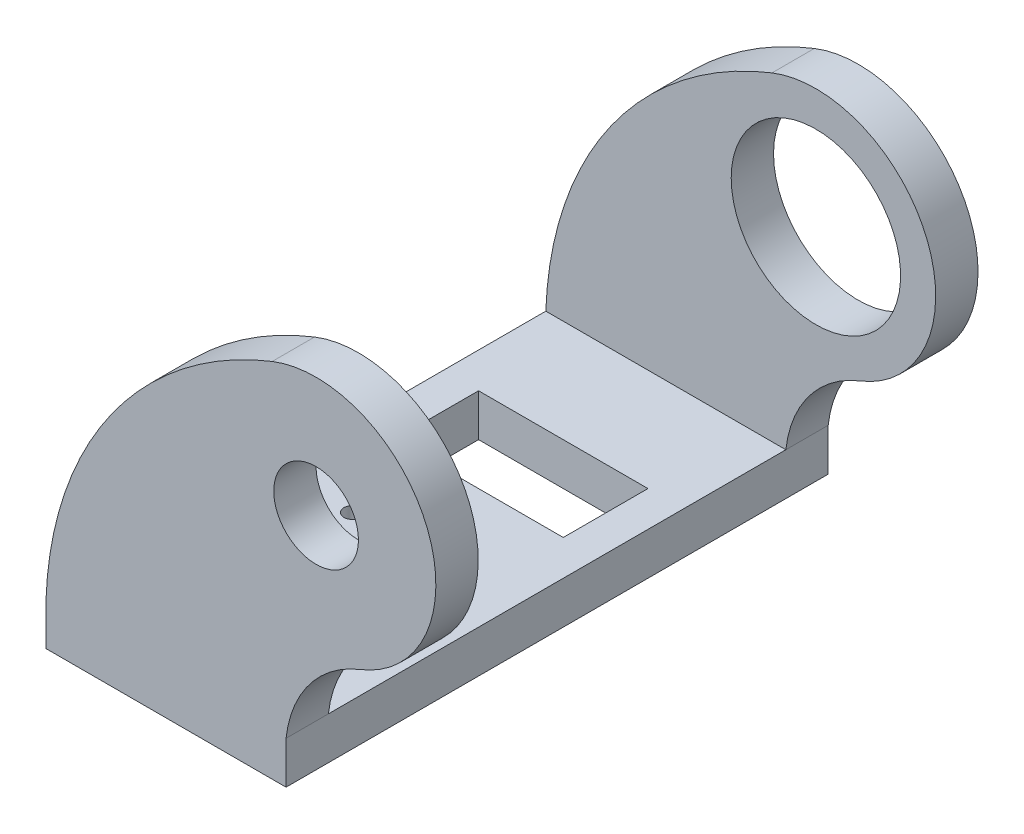
SolidWorks part; units mm, degrees
ref_plane "Front Plane" through (0, 0, 0) normal (0, 0, 1) x (1, 0, 0)
ref_plane "Top Plane" through (0, 0, 0) normal (0, 1, 0) x (1, 0, 0)
ref_plane "Right Plane" through (0, 0, 0) normal (1, 0, 0) x (0, 0, -1)
sketch "Model" plane through (0, 0, 0) normal (0, 0, 1) x (1, 0, 0)
  line L0 (25.204, 18.4188) -> (53.5459, 18.4188)
  arc A0 (51.9109, 56.1349) -> (25.204, 18.4188) centre (67.3687, 16.8755) ccw
  arc A1 (62.2731, 29.8172) -> (53.5459, 18.4188) centre (67.3687, 16.8755) ccw
  arc A2 (62.2731, 29.8172) -> (51.9109, 56.1349) centre (57.092, 42.9761) ccw
extrude "Boss-Extrude1" add sketch "Model" along normal blind 5
sketch "Sketch2" plane through (0, 0, 5) normal (0, 0, 1) x (1, 0, 0)
  circle A0 centre (57.092, 42.9761) radius 5
  dimension "D1" = 10
extrude "Cut-Extrude1" cut sketch "Sketch2" against normal blind 5
sketch "Sketch4" plane through (0, 18.4188, 0) normal (0, -1, 0) x (1, 0, 0)
  line L4 (25.204, 0) -> (53.5459, 0)
  line L5 (53.5459, 0) -> (53.5459, 5)
  line L6 (53.5459, 5) -> (25.204, 5)
  line L7 (25.204, 5) -> (25.204, 0)
  line L8 (25.204, 0) -> (53.5459, 0)
  line L9 (53.5459, 0) -> (53.5459, 5)
  line L10 (53.5459, 5) -> (25.204, 5)
  line L11 (25.204, 5) -> (25.204, 0)
  dimension "D1" = 0
extrude "Boss-Extrude2" add sketch "Sketch4" along normal blind 5
sketch "Sketch5" plane through (0, 0, 0) normal (0, 0, -1) x (-1, 0, 0)
  line L0 (-25.204, 13.4188) -> (-25.204, 18.4188) construction
  line L1 (-53.5459, 13.4188) -> (-25.204, 13.4188)
  line L2 (-53.5459, 13.4188) -> (-53.5459, 18.4188)
  line L3 (-53.5459, 18.4188) -> (-25.204, 18.4188)
  line L4 (-25.204, 13.4188) -> (-25.204, 18.4188)
extrude "Boss-Extrude3" add sketch "Sketch5" along normal blind 31.9
sketch "Sketch6" plane through (0, 18.4188, 0) normal (0, 1, 0) x (1, 0, 0)
  line L0 (39.3749, 31.9) -> (39.3749, 26.9) construction
  line L1 (25.204, 31.9) -> (53.5459, 31.9) construction
  line L3 (49.3749, 26.9) -> (29.3749, 26.9)
  line L4 (49.3749, 26.9) -> (49.3749, 31.9)
  line L5 (49.3749, 31.9) -> (29.3749, 31.9)
  line L6 (29.3749, 26.9) -> (29.3749, 31.9)
  line L7 (49.3749, 26.9) -> (29.3749, 31.9) construction
  line L8 (49.3749, 31.9) -> (29.3749, 26.9) construction
  point P4 (39.3749, 29.4)
extrude "Cut-Extrude3" cut sketch "Sketch6" against normal blind 5
sketch "Sketch8" plane through (0, 0, -31.9) normal (0, 0, -1) x (-1, 0, 0)
  line L1 (-53.5459, 18.4188) -> (-49.3749, 18.4188)
  line L2 (-53.5459, 18.4188) -> (-53.5459, 13.4188)
  line L3 (-53.5459, 13.4188) -> (-49.3749, 13.4188)
  line L4 (-25.204, 18.4188) -> (-29.3749, 18.4188)
  line L5 (-29.3749, 18.4188) -> (-29.3749, 13.4188)
  line L6 (-29.3749, 13.4188) -> (-25.204, 13.4188)
  line L7 (-25.204, 13.4188) -> (-25.204, 18.4188)
  line L8 (-25.204, 18.4188) -> (-29.3749, 18.4188)
  line L9 (-29.3749, 18.4188) -> (-29.3749, 13.4188)
  line L10 (-29.3749, 13.4188) -> (-25.204, 13.4188)
  line L11 (-25.204, 13.4188) -> (-25.204, 18.4188)
  line L12 (-49.3749, 18.4188) -> (-49.3749, 13.4188)
  dimension "D1" = 0
sketch "Sketch10" plane through (0, 18.4188, 0) normal (0, 1, 0) x (1, 0, 0)
  line L0 (39.3749, 26.9) -> (39.3749, 13.5) construction
  line L1 (29.3749, 26.9) -> (49.3749, 26.9) construction
  line L3 (44.3749, 10) -> (34.3749, 10) construction
  line L4 (44.3749, 10) -> (44.3749, 17) construction
  line L5 (44.3749, 17) -> (34.3749, 17) construction
  line L6 (34.3749, 10) -> (34.3749, 17) construction
  line L7 (44.3749, 10) -> (34.3749, 17) construction
  line L8 (44.3749, 17) -> (34.3749, 10) construction
  circle A0 centre (34.3749, 17) radius 1
  circle A1 centre (44.3749, 17) radius 1
  circle A2 centre (34.3749, 10) radius 1
  circle A3 centre (44.3749, 10) radius 1
extrude "Boss-Extrude8" add sketch "Sketch8" along normal blind 10
sketch "Sketch15" plane through (0, 0, -26.9) normal (0, 0, -1) x (-1, 0, 0)
  line L4 (-29.3749, 18.4188) -> (-49.3749, 18.4188)
  line L5 (-49.3749, 18.4188) -> (-49.3749, 13.4188)
  line L6 (-49.3749, 13.4188) -> (-29.3749, 13.4188)
  line L7 (-29.3749, 13.4188) -> (-29.3749, 18.4188)
  line L8 (-29.3749, 18.4188) -> (-49.3749, 18.4188)
  line L9 (-49.3749, 18.4188) -> (-49.3749, 13.4188)
  line L10 (-49.3749, 13.4188) -> (-29.3749, 13.4188)
  line L11 (-29.3749, 13.4188) -> (-29.3749, 18.4188)
  dimension "D1" = 0
extrude "Boss-Extrude9" add sketch "Sketch15" along normal blind 5
sketch "Sketch18" plane through (0, 0, -41.9) normal (0, 0, -1) x (-1, 0, 0)
  line L1 (-53.5459, 18.4188) -> (-25.204, 18.4188)
  line L2 (-53.5459, 18.4188) -> (-53.5459, 13.4188)
  line L3 (-53.5459, 13.4188) -> (-25.204, 13.4188)
  line L4 (-25.204, 18.4188) -> (-25.204, 13.4188)
extrude "Boss-Extrude11" add sketch "Sketch18" along normal blind 12.11
sketch "Sketch19" plane through (0, 18.4188, 0) normal (0, 1, 0) x (1, 0, 0)
  line L2 (39.3749, 26.9) -> (39.3749, 13.5) construction
  line L3 (39.3749, 31.9) -> (39.3749, 18.5) construction
  line L4 (29.3749, 31.9) -> (49.3749, 31.9) construction
  line L6 (44.3749, 15) -> (34.3749, 15) construction
  line L7 (44.3749, 15) -> (44.3749, 22) construction
  line L8 (44.3749, 22) -> (34.3749, 22) construction
  line L9 (34.3749, 15) -> (34.3749, 22) construction
  line L10 (44.3749, 15) -> (34.3749, 22) construction
  line L11 (44.3749, 22) -> (34.3749, 15) construction
  circle A0 centre (34.3749, 22) radius 1
  circle A1 centre (44.3749, 22) radius 1
  circle A2 centre (34.3749, 15) radius 1
  circle A3 centre (44.3749, 15) radius 1
extrude "Cut-Extrude6" cut sketch "Sketch19" against normal blind 12.11
sketch "Sketch20" plane through (0, 0, -54.01) normal (0, 0, -1) x (-1, 0, 0)
  line L1 (-53.5459, 18.4188) -> (-25.204, 18.4188)
  line L4 (-53.5459, 18.4188) -> (-53.5459, 13.4188)
  line L5 (-53.5459, 13.4188) -> (-25.204, 13.4188)
  line L6 (-25.204, 18.4188) -> (-25.204, 13.4188)
  circle A0 centre (-57.092, 42.9761) radius 10
  arc A3 (-25.204, 18.4188) -> (-51.9109, 56.1349) centre (-67.3687, 16.8755) ccw
  arc A4 (-51.9109, 56.1349) -> (-62.2731, 29.8172) centre (-57.092, 42.9761) ccw
  arc A5 (-53.5459, 18.4188) -> (-62.2731, 29.8172) centre (-67.3687, 16.8755) ccw
  arc A6 (-25.204, 18.4188) -> (-51.9109, 56.1349) centre (-67.3687, 16.8755) ccw
  arc A7 (-51.9109, 56.1349) -> (-62.2731, 29.8172) centre (-57.092, 42.9761) ccw
  arc A8 (-53.5459, 18.4188) -> (-62.2731, 29.8172) centre (-67.3687, 16.8755) ccw
  dimension "D1" = 0
extrude "Boss-Extrude12" add sketch "Sketch20" along normal blind 5
